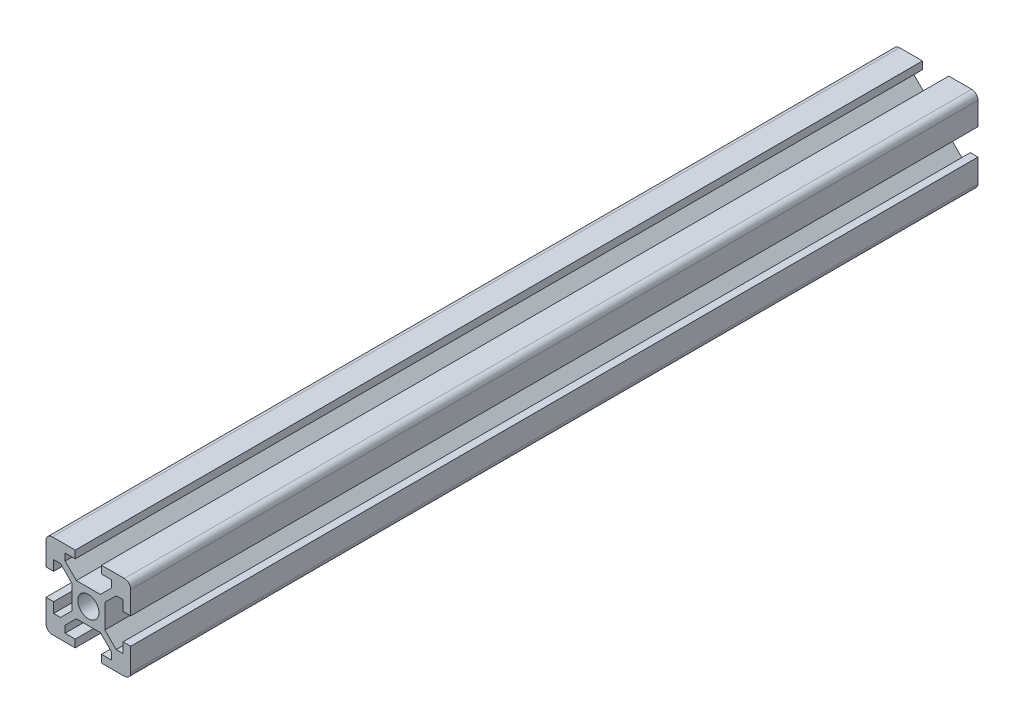
SolidWorks part; units mm, degrees
material "Alliage 1060"
ref_plane "Plan de face" through (0, 0, 0) normal (0, 0, 1) x (1, 0, 0)
ref_plane "Plan de dessus" through (0, 0, 0) normal (0, 1, 0) x (1, 0, 0)
ref_plane "Plan de droite" through (0, 0, 0) normal (1, 0, 0) x (0, 0, -1)
sketch "Esquisse1" plane through (0, 0, 0) normal (0, 0, 1) x (1, 0, 0)
  line L0 (-4716.2745, 0) -> (231097.4499, 0) construction
  line L1 (0, -4716.2745) -> (0, 231097.4499) construction
  line L2 (-3334.9097, 3334.9097) -> (163410.5739, -163410.5739) construction
  line L3 (-3334.9097, -3334.9097) -> (163410.5739, 163410.5739) construction
  line L4 (-3.1, -10) -> (-3.1, -8.2)
  line L5 (-3.1, -8.2) -> (-5.5, -8.2)
  line L6 (-5.5, -8.2) -> (-5.5, -6.5607)
  line L7 (-5.5, -6.5607) -> (-2.8393, -3.9)
  line L8 (-2.8393, -3.9) -> (2.8393, -3.9)
  line L9 (-3.1, -10) -> (-8.5, -10)
  line L10 (-10, -3.1) -> (-10, -8.5)
  line L11 (-10, -3.1) -> (-8.2, -3.1)
  line L12 (-8.2, -5.5) -> (-6.5607, -5.5)
  line L13 (-8.2, -3.1) -> (-8.2, -5.5)
  line L14 (-6.5607, -5.5) -> (-3.9, -2.8393)
  line L15 (-3.9, -2.8393) -> (-3.9, 2.8393)
  line L16 (5.5, -6.5607) -> (2.8393, -3.9)
  line L17 (5.5, -8.2) -> (5.5, -6.5607)
  line L18 (3.1, -8.2) -> (5.5, -8.2)
  line L19 (3.1, -10) -> (3.1, -8.2)
  line L20 (3.1, -10) -> (8.5, -10)
  line L21 (10, -3.1) -> (10, -8.5)
  line L22 (10, -3.1) -> (8.2, -3.1)
  line L23 (8.2, -3.1) -> (8.2, -5.5)
  line L24 (8.2, -5.5) -> (6.5607, -5.5)
  line L25 (6.5607, -5.5) -> (3.9, -2.8393)
  line L26 (3.9, -2.8393) -> (3.9, 2.8393)
  line L27 (6.5607, 5.5) -> (3.9, 2.8393)
  line L28 (8.2, 5.5) -> (6.5607, 5.5)
  line L29 (8.2, 3.1) -> (8.2, 5.5)
  line L30 (10, 3.1) -> (8.2, 3.1)
  line L31 (10, 3.1) -> (10, 8.5)
  line L32 (3.1, 10) -> (8.5, 10)
  line L33 (3.1, 10) -> (3.1, 8.2)
  line L34 (3.1, 8.2) -> (5.5, 8.2)
  line L35 (5.5, 8.2) -> (5.5, 6.5607)
  line L36 (5.5, 6.5607) -> (2.8393, 3.9)
  line L37 (-6.5607, 5.5) -> (-3.9, 2.8393)
  line L38 (-8.2, 3.1) -> (-8.2, 5.5)
  line L39 (-8.2, 5.5) -> (-6.5607, 5.5)
  line L40 (-10, 3.1) -> (-8.2, 3.1)
  line L41 (-10, 3.1) -> (-10, 8.5)
  line L42 (-3.1, 10) -> (-8.5, 10)
  line L43 (-2.8393, 3.9) -> (2.8393, 3.9)
  line L44 (-5.5, 6.5607) -> (-2.8393, 3.9)
  line L45 (-5.5, 8.2) -> (-5.5, 6.5607)
  line L46 (-3.1, 8.2) -> (-5.5, 8.2)
  line L47 (-3.1, 10) -> (-3.1, 8.2)
  arc A0 (-10, -8.5) -> (-8.5, -10) centre (-8.5, -8.5) ccw
  arc A1 (10, -8.5) -> (8.5, -10) centre (8.5, -8.5) cw
  arc A2 (10, 8.5) -> (8.5, 10) centre (8.5, 8.5) ccw
  arc A3 (-10, 8.5) -> (-8.5, 10) centre (-8.5, 8.5) cw
  circle A4 centre (0, 0) radius 2.5
  point P8 (-3.1, -10)
  point P25 (-10, -10)
  point P27 (0, -3.9)
  point P41 (-3.9, 0)
  point P42 (3.9, 0)
  point P66 (0, 3.9)
  point P67 (-10, 10)
  point P68 (-3.1, 10)
  dimension "D4" = 1.5
  dimension "D6" = 5
  dimension "D1" = 3.1
  dimension "D2" = 10
  dimension "D3" = 1.8
  dimension "1.5/2" = 0.75
  dimension "D5" = 5.5
  dimension "D7" = 6.1
extrude "Boss.-Extru.1" add sketch "Esquisse1" along normal blind 200
